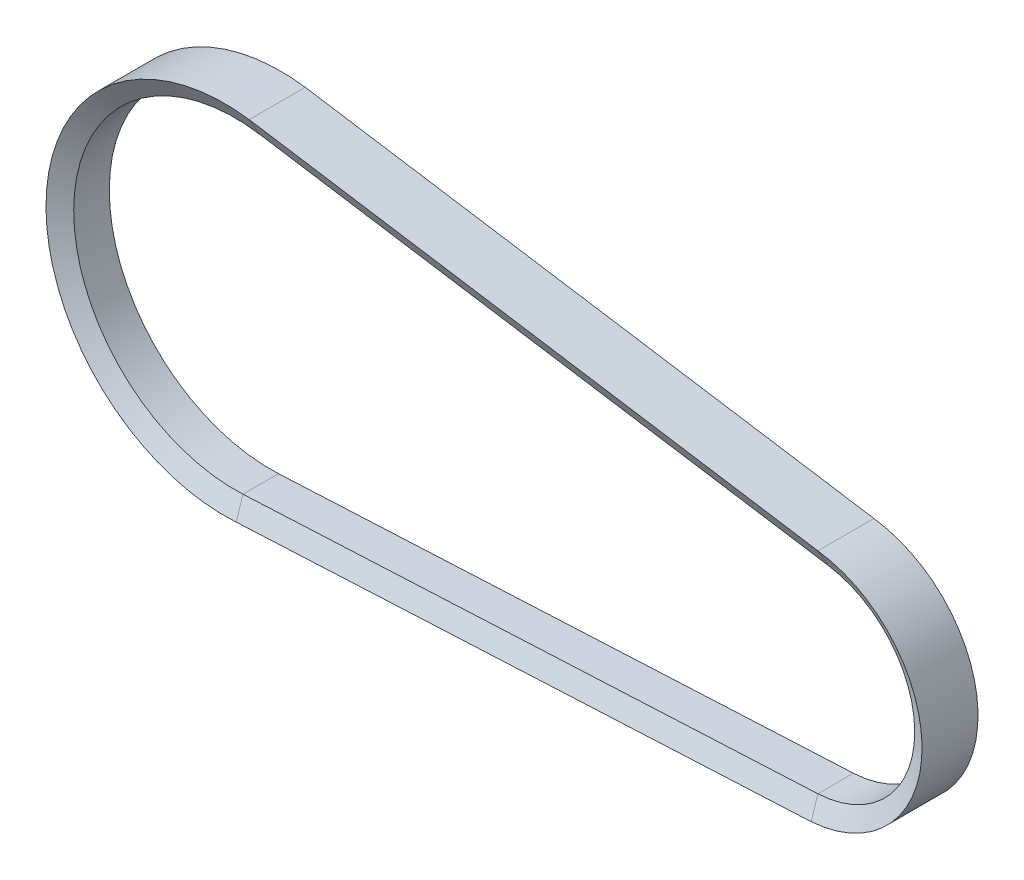
SolidWorks part; units mm, degrees
ref_plane "Front Plane" through (0, 0, 0) normal (0, 0, 1) x (1, 0, 0)
ref_plane "Top Plane" through (0, 0, 0) normal (0, 1, 0) x (1, 0, 0)
ref_plane "Right Plane" through (0, 0, 0) normal (1, 0, 0) x (0, 0, -1)
sketch "Sketch2" plane through (0, 0, 0) normal (0, 0, 1) x (1, 0, 0)
  line L0 (0, 0) -> (1, 0) construction
  line L1 (0, 0) -> (0, 1) construction
  line L2 (8.3592, 53.3491) -> (201.2582, 23.1238)
  line L3 (197.651, -44.426) -> (2.6301, -53.9359)
  arc A0 (2.6301, -53.9359) -> (8.3592, 53.3491) centre (0, 0) cw
  arc A1 (201.2582, 23.1238) -> (197.651, -44.426) centre (195.995, -10.4664) cw
ref_plane "Plane1" through (8.3592, 0, 0) normal (1, 0, 0) x (0, 0, -1)
sketch "Sketch3" plane through (8.3592, 0, 0) normal (1, 0, 0) x (0, 0, -1)
  line L0 (-6.035, 54) -> (6.035, 54)
  line L2 (0, 54) -> (0, -54) construction
  line L3 (6.035, 54) -> (9.4991, 60)
  line L4 (9.4991, 60) -> (-9.4991, 60)
  line L5 (-9.4991, 60) -> (-6.035, 54)
  dimension "D1" = 12.07
  dimension "D2" = 90
  dimension "D3" = 6.035
  dimension "D4" = 54
  dimension "D5" = 6
  dimension "D6" = 60
  dimension "D7" = 60
sweep "Sweep1" add profiles "Sketch3" path "Sketch2"
